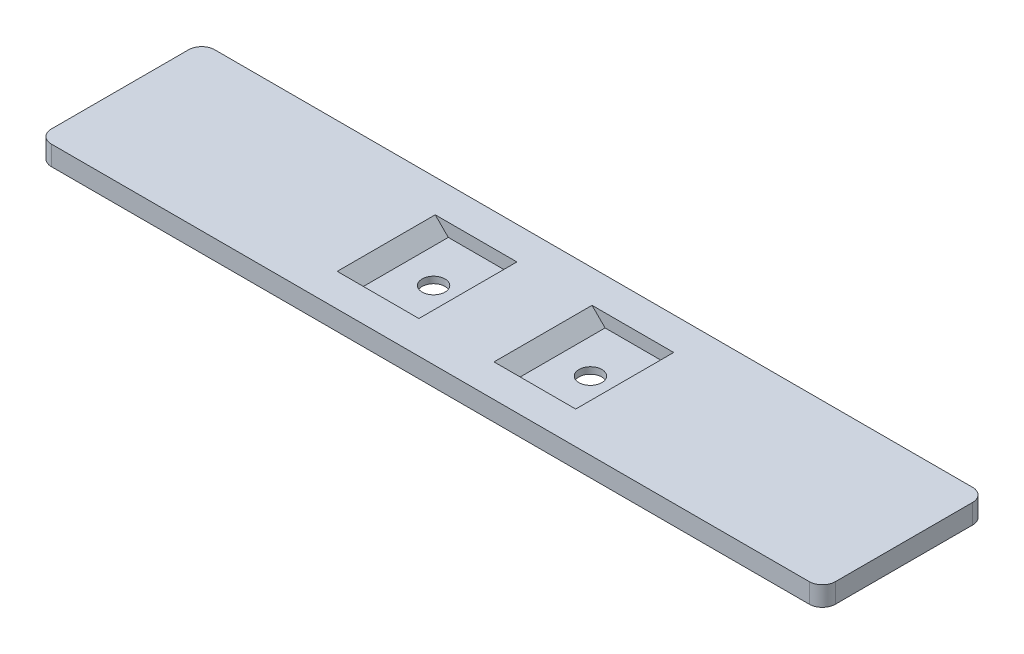
SolidWorks part; units mm, degrees
ref_plane "Front Plane" through (0, 0, 0) normal (0, 0, 1) x (1, 0, 0)
ref_plane "Top Plane" through (0, 0, 0) normal (0, 1, 0) x (1, 0, 0)
ref_plane "Right Plane" through (0, 0, 0) normal (1, 0, 0) x (0, 0, -1)
sketch "Top Cover" plane through (0, 0, 0) normal (0, 1, 0) x (1, 0, 0)
  line L1 (60, -12.5) -> (-60, -12.5)
  line L2 (60, -12.5) -> (60, 12.5)
  line L3 (60, 12.5) -> (-60, 12.5)
  line L4 (-60, -12.5) -> (-60, 12.5)
  line L5 (60, -12.5) -> (-60, 12.5) construction
  line L6 (60, 12.5) -> (-60, -12.5) construction
  point P0 (0, 0)
  dimension "D1" = 25
  dimension "D2" = 120
extrude "Boss-Extrude1" add sketch "Top Cover" along normal blind 3
sketch "Attachment Point" plane through (0, 3, 0) normal (0, 1, 0) x (1, 0, 0)
  line L0 (-60, 0) -> (60, 0) construction
  line L1 (-17.25, 7.5) -> (-6.75, 7.5)
  line L2 (-17.25, 7.5) -> (-17.25, -7.5)
  line L3 (-17.25, -7.5) -> (-6.75, -7.5)
  line L4 (-6.75, 7.5) -> (-6.75, -7.5)
  line L5 (-17.25, 7.5) -> (-6.75, -7.5) construction
  line L6 (-17.25, -7.5) -> (-6.75, 7.5) construction
  line L7 (-60, 12.5) -> (-60, -12.5) construction
  line L8 (60, -12.5) -> (60, 12.5) construction
  line L9 (0, -12.5) -> (0, -7.5) construction
  line L10 (-60, -12.5) -> (60, -12.5) construction
  line L11 (17.25, -7.5) -> (6.75, 7.5) construction
  line L12 (17.25, 7.5) -> (6.75, -7.5) construction
  line L13 (6.75, 7.5) -> (6.75, -7.5)
  line L14 (17.25, -7.5) -> (6.75, -7.5)
  line L15 (17.25, 7.5) -> (17.25, -7.5)
  line L16 (17.25, 7.5) -> (6.75, 7.5)
  point P0 (-12, 0)
  dimension "D1" = 12
  dimension "D2" = 10.5
  dimension "D3" = 15
extrude "Cut-Extrude1" cut sketch "Attachment Point" against normal blind 2
sketch "Sketch4" plane through (0, 3, 0) normal (0, 1, 0) x (1, 0, 0)
  line L0 (0, -12.5) -> (0, -3.0256) construction
  line L1 (-60, -12.5) -> (60, -12.5) construction
  line L2 (-60, 0) -> (-44.806, 0) construction
  line L3 (-60, 12.5) -> (-60, -12.5) construction
  line L4 (-12, 7.5) -> (-12, -7.5) construction
  line L5 (-6.75, 7.5) -> (-17.25, 7.5) construction
  line L6 (-17.25, -7.5) -> (-6.75, -7.5) construction
  circle A0 centre (-12, 0) radius 1.75
  circle A1 centre (12, 0) radius 1.75
  dimension "D1" = 3.5
extrude "M3 Screw CUT" cut sketch "Sketch4" against normal through all
fillet "Fillet1" radius 2 1 edges at (-60, 1.5, 12.5)
fillet "Fillet2" radius 2 1 edges at (60, 1.5, 12.5)
fillet "Fillet3" radius 2 1 edges at (60, 1.5, -12.5)
fillet "Fillet4" radius 2 1 edges at (-60, 1.5, -12.5)
sketch "Sketch5" plane through (0, 3, 0) normal (0, 1, 0) x (1, 0, 0)
  line L1 (6.75, -7.5) -> (3.75, -7.5)
  line L2 (6.75, -7.5) -> (6.75, 7.5)
  line L3 (6.75, 7.5) -> (3.75, 7.5)
  line L4 (3.75, -7.5) -> (3.75, 7.5)
  line L5 (-17.25, -7.5) -> (-20.25, -7.5)
  line L6 (-17.25, -7.5) -> (-17.25, 7.5)
  line L7 (-17.25, 7.5) -> (-20.25, 7.5)
  line L8 (-20.25, -7.5) -> (-20.25, 7.5)
  dimension "D1" = 3
extrude "Cut-Extrude3" cut sketch "Sketch5" against normal up to surface (2 mm away) up to face at (12, 1, -1.75)
sketch "Sketch6" plane through (0, 0, 7.5) normal (0, 0, -1) x (-1, 0, 0)
  line L0 (-4.75, 3) -> (-6.75, 1)
  line L1 (-3.75, 1) -> (-17.25, 1) construction
  line L2 (-6.75, 1) -> (-3.75, 1)
  line L3 (-3.75, 1) -> (-3.75, 3)
  line L4 (-3.75, 3) -> (-4.75, 3)
  line L5 (-3.75, 3) -> (-17.25, 3) construction
  dimension "D1" = 10.5
  dimension "D2" = 45
extrude "Connetor 1 Angle" add sketch "Sketch6" along normal up to surface (15 mm away) up to face at (10.5, 2, -7.5)
sketch "Sketch7" plane through (0, 0, 7.5) normal (0, 0, -1) x (-1, 0, 0)
  line L0 (19.25, 3) -> (17.25, 1)
  line L1 (20.25, 1) -> (6.75, 1) construction
  line L2 (20.25, 3) -> (20.25, 1)
  line L3 (20.25, 1) -> (17.25, 1)
  line L4 (20.25, 3) -> (19.25, 3)
  line L5 (20.25, 3) -> (6.75, 3) construction
  dimension "D1" = 10.5
  dimension "D2" = 45
extrude "Connector 2 Angle" add sketch "Sketch7" along normal up to surface (15 mm away) up to face at (-13.5, 2, -7.5)
